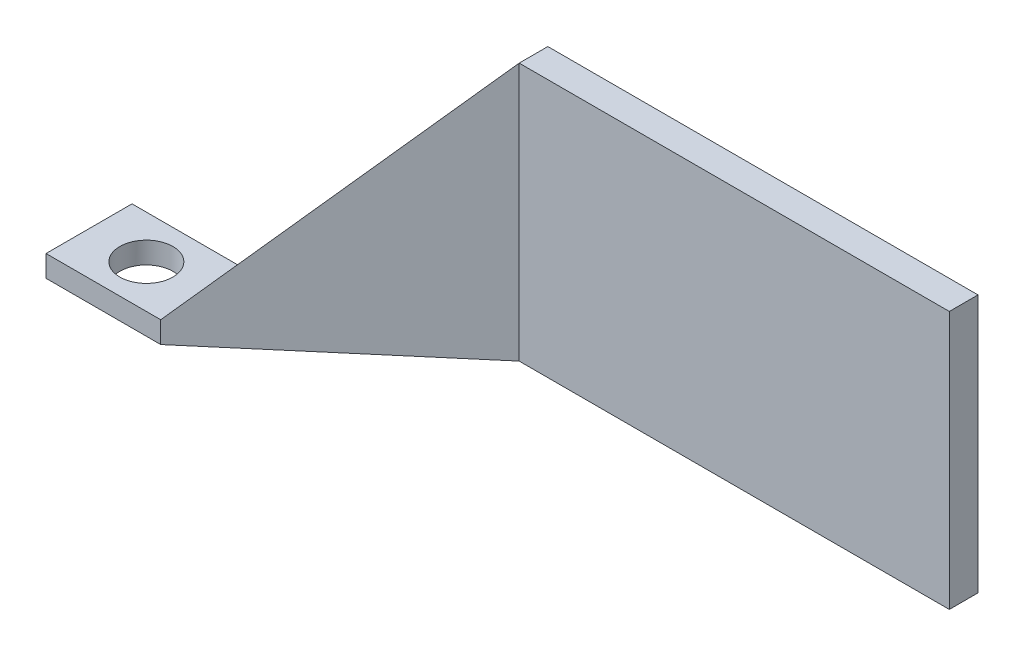
SolidWorks part; units mm, degrees
ref_plane "前视基准面" through (0, 0, 0) normal (0, 0, 1) x (1, 0, 0)
ref_plane "上视基准面" through (0, 0, 0) normal (0, 1, 0) x (1, 0, 0)
ref_plane "右视基准面" through (0, 0, 0) normal (1, 0, 0) x (0, 0, -1)
sketch "草图1" plane through (0, 0, 0) normal (0, 0, 1) x (1, 0, 0)
  line L0 (0, 0) -> (-8, 0)
  line L1 (-8, 0) -> (-8, -1.5)
  line L2 (-8, -1.5) -> (0, -1.5)
  line L3 (0, -1.5) -> (0, 0)
  dimension "D1" = 8
  dimension "D2" = 1.5
extrude "凸台-拉伸1" add sketch "草图1" along normal blind 6
sketch "草图2" plane through (0, 0, 0) normal (0, 1, 0) x (1, 0, 0)
  line L0 (0, 0) -> (-8, 0) construction
  line L1 (15, 6) -> (45, 6)
  line L2 (15, 6) -> (15, 4)
  line L3 (15, 4) -> (45, 4)
  line L4 (45, 6) -> (45, 4)
  line L5 (0, -6) -> (0, 0) construction
  dimension "D1" = 4
  dimension "D2" = 2
  dimension "D3" = 30
  dimension "D4" = 15
extrude "凸台-拉伸2" add sketch "草图2" along normal blind 18 separate body
loft "放样1" add section face at (15, 9, -5) section face at (0, -0.75, 3)
sketch "草图3" plane through (0, 0, 0) normal (0, 1, 0) x (1, 0, 0)
  line L0 (0, 0) -> (-8, 0) construction
  line L1 (-8, -6) -> (-8, 0) construction
  circle A0 centre (-4, -3) radius 1.85
  point P5 (-4, 0)
  point P8 (-8, -3)
  dimension "D1" = 3.7
extrude "切除-拉伸1" cut sketch "草图3" against normal blind 6
